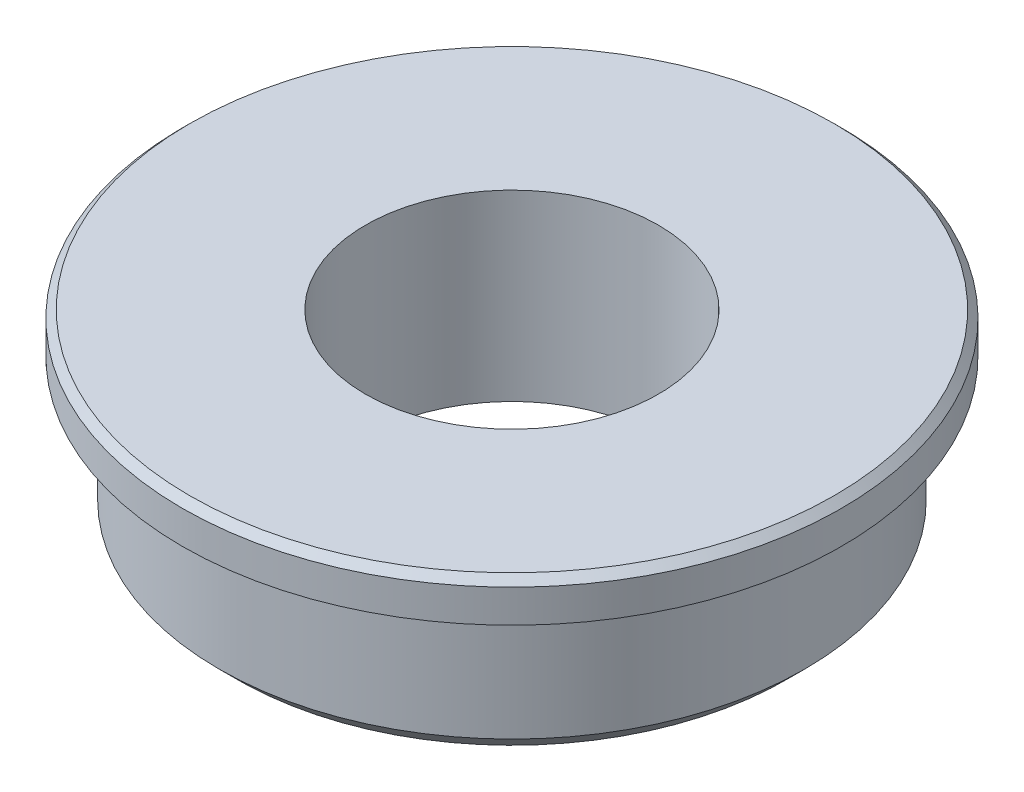
SolidWorks part; units mm, degrees
material "合金钢"
ref_plane "前视基准面" through (0, 0, 0) normal (0, 0, 1) x (1, 0, 0)
ref_plane "上视基准面" through (0, 0, 0) normal (0, 1, 0) x (1, 0, 0)
ref_plane "右视基准面" through (0, 0, 0) normal (1, 0, 0) x (0, 0, -1)
sketch "草图1" plane through (0, 0, 0) normal (0, 0, 1) x (1, 0, 0)
  line L0 (0, 10.7564) -> (0, -8.2308) construction
  line L1 (-11.5551, 0) -> (13.5519, 0) construction
  line L2 (-4, 0) -> (-8, 0)
  line L3 (-8, 0) -> (-8, 3.9)
  line L4 (-8, 3.9) -> (-9, 3.9)
  line L5 (-9, 3.9) -> (-9, 5)
  line L6 (-9, 5) -> (-4, 5)
  line L7 (-4, 5) -> (-4, 0)
  dimension "D1" = 4
  dimension "D2" = 8
  dimension "D3" = 9
  dimension "D4" = 5
  dimension "D5" = 1.1
revolve "旋转1" add sketch "草图1" angle 360 about L0
chamfer "倒角1" distance 0.5 angle 45 1 edges at (0, 0, 8)
chamfer "倒角2" distance 0.2 angle 45 1 edges at (0, 5, 9)
